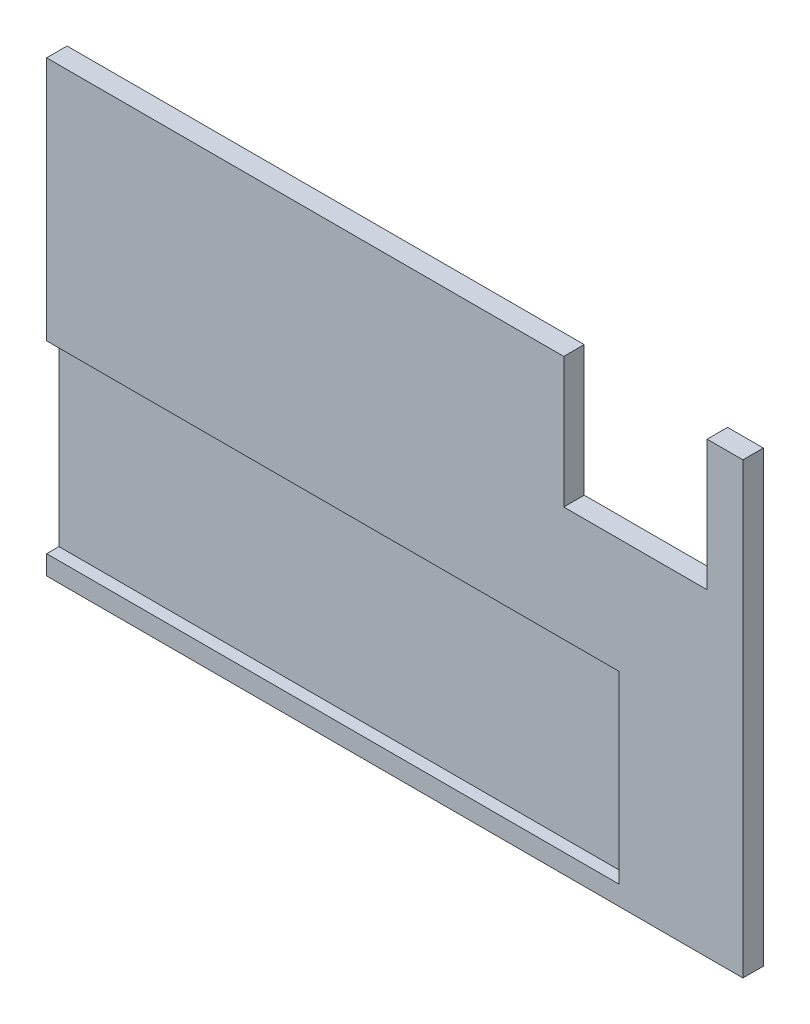
SolidWorks part; units mm, degrees
ref_plane "Front Plane" through (0, 0, 0) normal (0, 0, 1) x (1, 0, 0)
ref_plane "Top Plane" through (0, 0, 0) normal (0, 1, 0) x (1, 0, 0)
ref_plane "Right Plane" through (0, 0, 0) normal (1, 0, 0) x (0, 0, -1)
sketch "Sketch1" plane through (0, 0, 0) normal (0, 0, 1) x (1, 0, 0)
  line L0 (0, -2.7182) -> (-101.2595, -2.7182)
  line L1 (-101.2595, -2.7182) -> (-101.2595, 106.8407)
  line L2 (-101.2595, 106.8407) -> (68.7405, 106.8407)
  line L3 (68.7405, 106.8407) -> (68.7405, -2.7182)
  line L4 (68.7405, -2.7182) -> (0, -2.7182)
  dimension "D1" = 170
  dimension "D2" = 109.5589
extrude "Boss-Extrude1" add sketch "Sketch1" along normal blind 5
sketch "Sketch2" plane through (0, 0, 5) normal (0, 0, 1) x (1, 0, 0)
  line L1 (-101.52, 47) -> (38.48, 47)
  line L2 (-101.52, 47) -> (-101.52, 2)
  line L3 (-101.52, 2) -> (38.48, 2)
  line L4 (38.48, 47) -> (38.48, 2)
  point P4 (0, 0)
  dimension "D1" = 140
  dimension "D2" = 45
extrude "Cut-Extrude1" cut sketch "Sketch2" against normal blind 3
sketch "Sketch3" plane through (0, 0, 0) normal (0, 0, 1) x (1, 0, 0)
  line L1 (25, 107) -> (60, 107)
  line L2 (25, 107) -> (25, 75)
  line L3 (25, 75) -> (60, 75)
  line L4 (60, 107) -> (60, 75)
  point P4 (0, 0)
  point P5 (0, 0)
  point P6 (0, 0)
  point P7 (0, 0)
  point P8 (0, 0)
extrude "Cut-Extrude3" cut sketch "Sketch3" along normal through all
